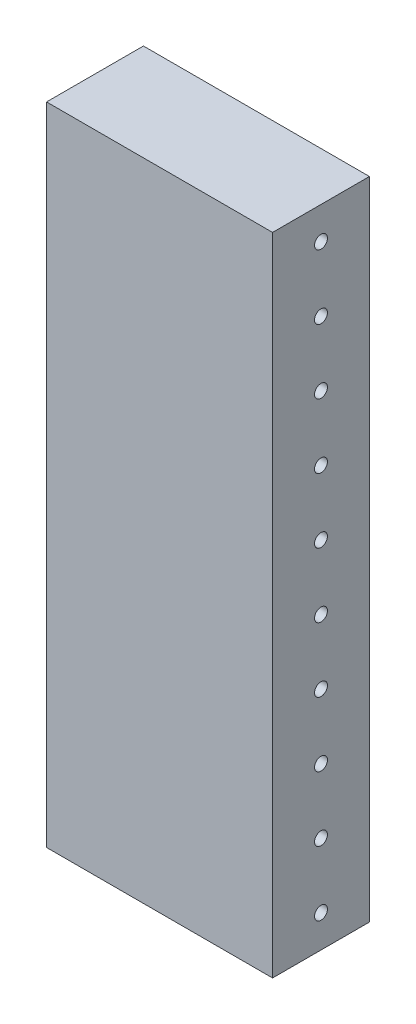
SolidWorks part; units mm, degrees
material "Balsa"
ref_plane "Front Plane" through (0, 0, 0) normal (0, 0, 1) x (1, 0, 0)
ref_plane "Top Plane" through (0, 0, 0) normal (0, 1, 0) x (1, 0, 0)
ref_plane "Right Plane" through (0, 0, 0) normal (1, 0, 0) x (0, 0, -1)
sketch "Sketch1" plane through (0, 0, 0) normal (0, 1, 0) x (1, 0, 0)
  line L1 (0, 0) -> (88.9, 0)
  line L2 (0, 0) -> (0, -38.1)
  line L3 (0, -38.1) -> (88.9, -38.1)
  line L4 (88.9, 0) -> (88.9, -38.1)
  dimension "D1" = 88.9
  dimension "D2" = 38.1
extrude "Boss-Extrude1" add sketch "Sketch1" along normal blind 254
sketch "Sketch2" plane through (0, 0, 0) normal (-1, 0, 0) x (0, 0, 1)
  line L1 (19.05, 12.7) -> (19.05, 38.1) construction
  line L3 (0, 0) -> (38.1, 0) construction
  line L4 (0, 254) -> (0, 0) construction
  circle A0 centre (19.05, 12.7) radius 2.54
  circle A8 centre (19.05, 38.1) radius 2.54
  circle A9 centre (19.05, 63.5) radius 2.54
  circle A10 centre (19.05, 88.9) radius 2.54
  circle A11 centre (19.05, 114.3) radius 2.54
  circle A12 centre (19.05, 139.7) radius 2.54
  circle A13 centre (19.05, 165.1) radius 2.54
  circle A14 centre (19.05, 190.5) radius 2.54
  circle A15 centre (19.05, 215.9) radius 2.54
  circle A16 centre (19.05, 241.3) radius 2.54
  dimension "D1" = 5.08
  dimension "D2" = 12.7
  dimension "D3" = 19.05
  dimension "D9" = 10
  dimension "D10" = 25.4
extrude "Cut-Extrude1" cut sketch "Sketch2" against normal through all
